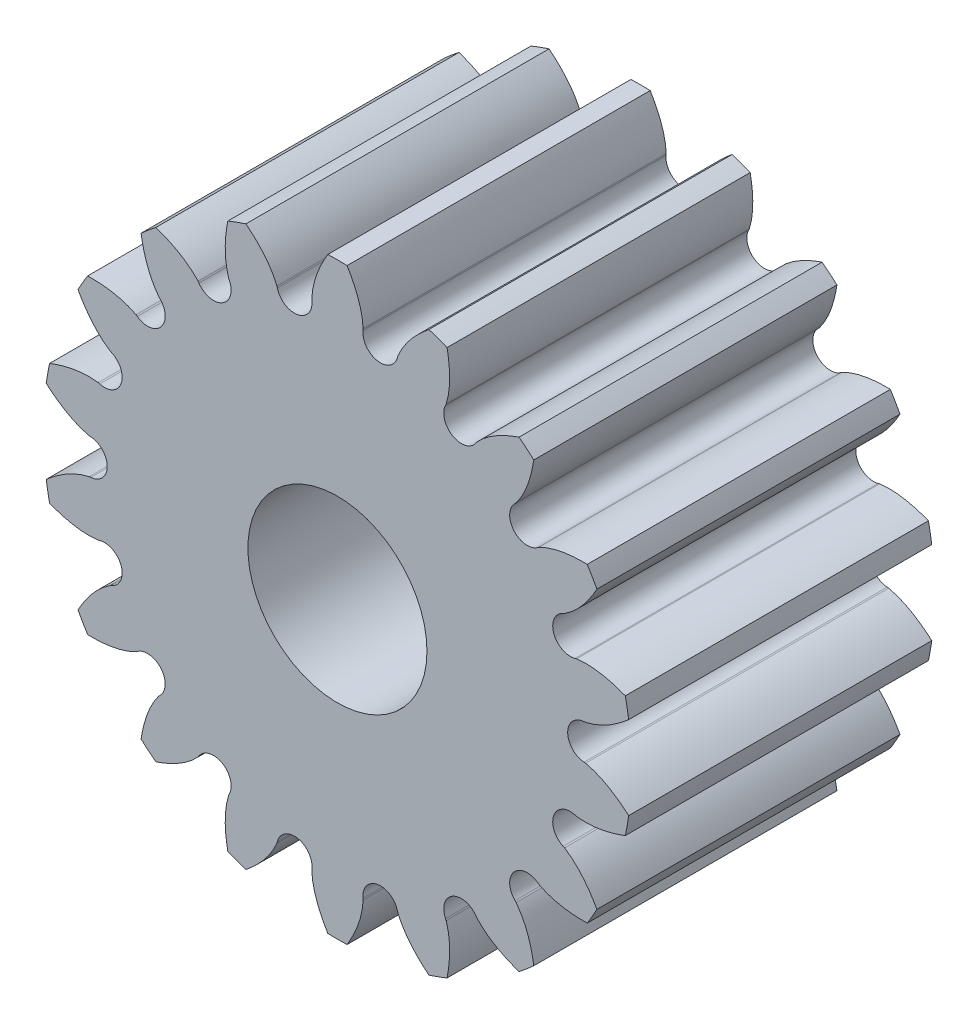
SolidWorks part; units mm, degrees
material "PE Low/Medium Density"
ref_plane "Front Plane" through (0, 0, 0) normal (0, 0, 1) x (1, 0, 0)
ref_plane "Top Plane" through (0, 0, 0) normal (0, 1, 0) x (1, 0, 0)
ref_plane "Right Plane" through (0, 0, 0) normal (1, 0, 0) x (0, 0, -1)
sketch "Involute construction sketch" plane through (0, 0, 0) normal (0, 0, 1) x (1, 0, 0)
  line L0 (0, 0) -> (-1.8157, 1.6751) construction
  line L1 (0, 0) -> (-1.2188, 2.1487) construction
  line L2 (0, 0) -> (-0.506, 2.418) construction
  line L3 (0, 0) -> (0.255, 2.4572) construction
  line L4 (-2.4509, 0.3098) -> (-2.2398, 1.042) construction
  line L5 (-2.2398, 1.042) -> (-1.8157, 1.6751) construction
  line L6 (-1.8157, 1.6751) -> (-1.2188, 2.1487) construction
  line L7 (0, 0) -> (-2.2398, 1.042) construction
  line L8 (0, 0) -> (-2.4509, 0.3098) construction
  line L9 (-1.2188, 2.1487) -> (-0.506, 2.418) construction
  line L10 (-0.506, 2.418) -> (0.255, 2.4572) construction
  line L11 (-2.4509, 0.3098) -> (-1.9731, 4.0897) construction
  line L12 (-2.2398, 1.042) -> (-0.9542, 3.8056) construction
  line L13 (-1.8157, 1.6751) -> (-0.2657, 3.3553) construction
  line L14 (-1.2188, 2.1487) -> (0.1068, 2.9007) construction
  line L15 (-0.506, 2.418) -> (0.2399, 2.5741) construction
  line L17 (0, 0) -> (0, 5.7859) construction
  line L18 (0, 0) -> (0.2291, 2.6189) construction
  line L19 (0, 0) -> (0.397, 2.2513) construction
  circle A0 centre (0, 0) radius 2.286 construction
  circle A1 centre (0, 0) radius 2.4704 construction
  circle A2 centre (0, 0) radius 2.6289 construction
  circle A3 centre (0, 0) radius 2.921 construction
  spline S0 degree 3 poles (0.255, 2.4572) (0.2476, 2.615) (0.11, 2.9502) (-0.5314, 3.7068) (-1.3595, 4.0133) (-1.9731, 4.0897) knots 0 0 0 0 0.160126 0.360107 1 1 1 1 construction
  point P17 (0.0957, 2.9194)
  dimension "D1" = 4.572
  dimension "D2" = 4.9407
  dimension "D3" = 5.2578
  dimension "D4" = 5.842
  dimension "D5" = 0.762
  dimension "D6" = 1.524
  dimension "D7" = 2.286
  dimension "D8" = 3.048
  dimension "D9" = 3.81
  dimension "D10" = 5
  dimension "D11" = 10
sketch "Sketch2" plane through (0, 0, 0) normal (0, 0, 1) x (1, 0, 0)
  line L0 (0, 2.921) -> (0, 2.286)
  line L1 (0, 0) -> (0, 5.7859) construction
  line L2 (0.255, 2.4572) -> (0.2534, 2.4415)
  line L3 (0, 0) -> (0.255, 2.4572) construction
  circle A0 centre (0, 0) radius 2.921 construction
  circle A1 centre (0, 0) radius 2.286 construction
  arc A2 (0, 2.921) -> (0.0957, 2.9194) centre (0, 0) cw
  arc A3 (0, 2.286) -> (0.397, 2.2513) centre (0, 0) cw
  arc A4 (0.2534, 2.4415) -> (0.397, 2.2513) centre (0.4273, 2.4235) ccw
  spline S0 degree 3 poles (0.255, 2.4572) (0.2525, 2.512) (0.2249, 2.6747) (0.152, 2.8255) (0.0957, 2.9194) knots 0 0 0 0 0.332628 1 1 1 1
sketch "Sketch3" plane through (0, 0, 0) normal (0, 0, 1) x (1, 0, 0)
  circle A0 centre (0, 0) radius 2.286
  circle A1 centre (0, 0) radius 0.889
  dimension "D1" = 4.572
  dimension "D2" = 1.778
extrude "Base" add sketch "Sketch3" along normal blind 3.0099
extrude "Half tooth" add sketch "Sketch2" along normal up to surface (3.0099 mm away) up to face at (2.286, 0, 3.0099)
ref_plane "Midplane of half tooth" through (0, 0, 0) normal (-1, 0, 0) x (0, 0, 1)
mirror "Mirror of half tooth" about plane through (0, 0, 0) normal (-1, 0, 0) of "Half tooth"
pattern_circular "Pattern of tooth" count 18 over 360 of "Half tooth", "Mirror of half tooth"
equation "\"radtodeg\"= 180 / PI'radian to degree conversion [ ]"
equation "\"phi\"= 20'pressure angle [deg]"
equation "\"N\"= 18'number of teeth [teeth]"
equation "\"A\"= 0.230in'diameter of addendum circle [inch]"
equation "\"B\"= 0.18in'diameter of dedendum circle [inch]"
equation "\"P\"= ( \"N\" + 2 ) / \"A\"'diametral pitch [teeth/inch]"
equation "\"d\"= \"N\" / \"P\"'diameter of pitch circle [inch]"
equation "\"cp\"= PI / \"P\"'circular pitch [inch/teeth]"
equation "\"add\"= 1 / \"P\"'addendum [inch]"
equation "\"ded\"= - ( \"B\" - \"d\" ) / 2'dedendum [inch]"
equation "\"clear\"= \"ded\" - \"add\"'clearance [inch]"
equation "\"C\"= \"B\" + 2 * \"clear\"'diameter of clearance circle [inch]"
equation "\"h\"= \"add\" + \"ded\"'tooth height / whole depth [inch]"
equation "\"s\"= \"d\" * cos ( \"phi\" * 1 / \"radtodeg\" )'diameter of base circle [inch]"
equation "\"t\"= ( PI / 2 ) / \"P\"'tooth width at diameter of pitch circle diameter [inch]"
equation "\"alpha\"= ( \"t\" / ( \"d\" / 2 ) * \"radtodeg\" ) / 2'arc angle for half of tooth width at pitch circle diameter [inch]"
equation "\"bore\"= 0.07'bore of hub [inch]"
equation "\"D4@Involute construction sketch\"= \"A\"'addendum circle"
equation "\"D3@Involute construction sketch\"= \"d\"'pitch circle"
equation "\"D2@Involute construction sketch\"= \"s\"'base circle"
equation "\"D1@Involute construction sketch\"= \"B\"'dedendum circle"
equation "\"seg\"= \"D5@Involute construction sketch\"'size of one involute segment [inch]"
equation "\"D6@Involute construction sketch\"=2*\"seg\""
equation "\"D7@Involute construction sketch\"=3*\"seg\""
equation "\"D8@Involute construction sketch\"=4*\"seg\""
equation "\"D9@Involute construction sketch\"=5*\"seg\""
equation "\"D10@Involute construction sketch\"=\"alpha\""
equation "\"D11@Involute construction sketch\"=2*\"alpha\""
equation "\"D1@Sketch3\"=\"B\""
equation "\"D2@Sketch3\"=\"bore\""
